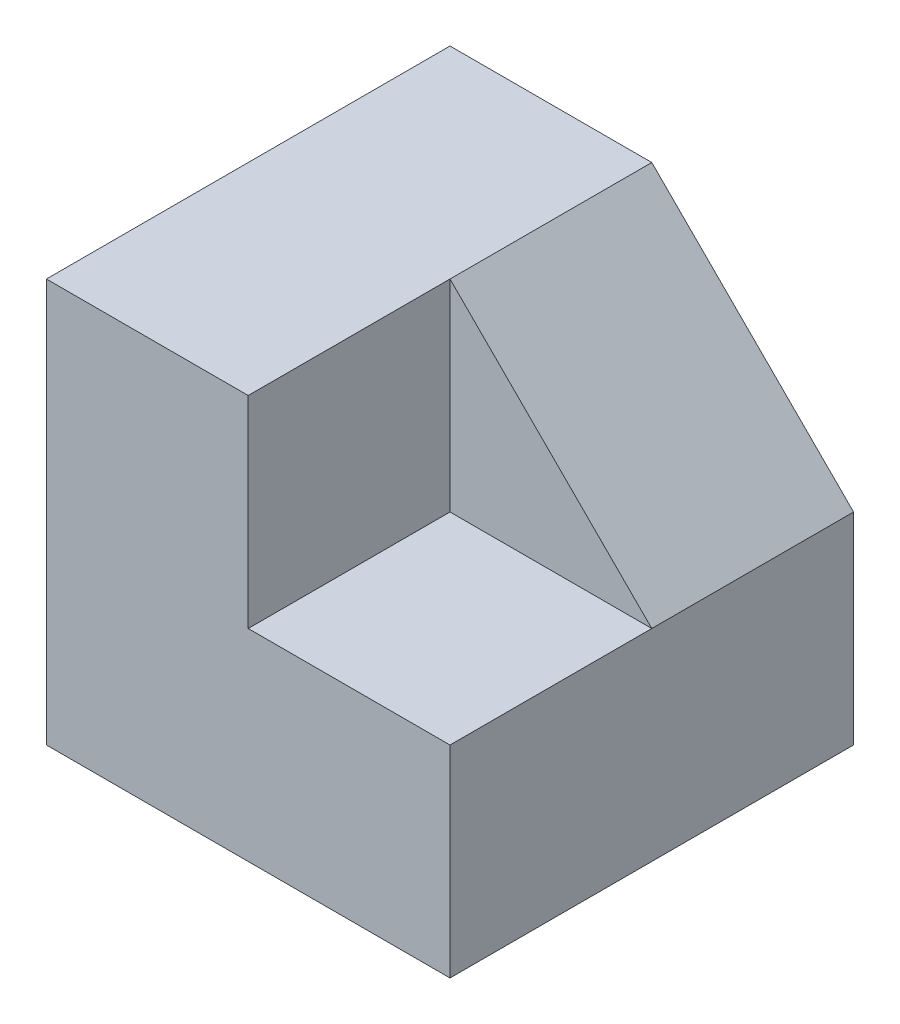
SolidWorks part; units mm, degrees
ref_plane "Alzado" through (0, 0, 0) normal (0, 0, 1) x (1, 0, 0)
ref_plane "Planta" through (0, 0, 0) normal (0, 1, 0) x (1, 0, 0)
ref_plane "Vista lateral" through (0, 0, 0) normal (1, 0, 0) x (0, 0, -1)
sketch "Croquis1" plane through (0, 0, 0) normal (0, 0, 1) x (1, 0, 0)
  line L0 (0, 0) -> (60, 0)
  line L1 (60, 0) -> (60, 60)
  line L2 (60, 60) -> (0, 60)
  line L3 (0, 60) -> (0, 0)
  dimension "D1" = 60
  dimension "D2" = 60
extrude "Saliente-Extruir1" add sketch "Croquis1" against normal blind 60
sketch "Croquis2" plane through (0, 60, 0) normal (0, 1, 0) x (1, 0, 0)
  line L0 (30, 0) -> (30, 30)
  line L1 (60, 0) -> (0, 0) construction
  line L2 (30, 30) -> (60, 30)
  line L3 (60, 60) -> (60, 0) construction
  line L4 (60, 30) -> (60, 0)
  line L5 (60, 0) -> (30, 0)
extrude "Cortar-Extruir1" cut sketch "Croquis2" against normal blind 30
sketch "Croquis3" plane through (0, 0, -30) normal (0, 0, 1) x (1, 0, 0)
  line L0 (60, 30) -> (30, 60)
  line L1 (30, 60) -> (60, 60)
  line L2 (60, 60) -> (60, 30)
extrude "Cortar-Extruir2" cut sketch "Croquis3" against normal blind 30
